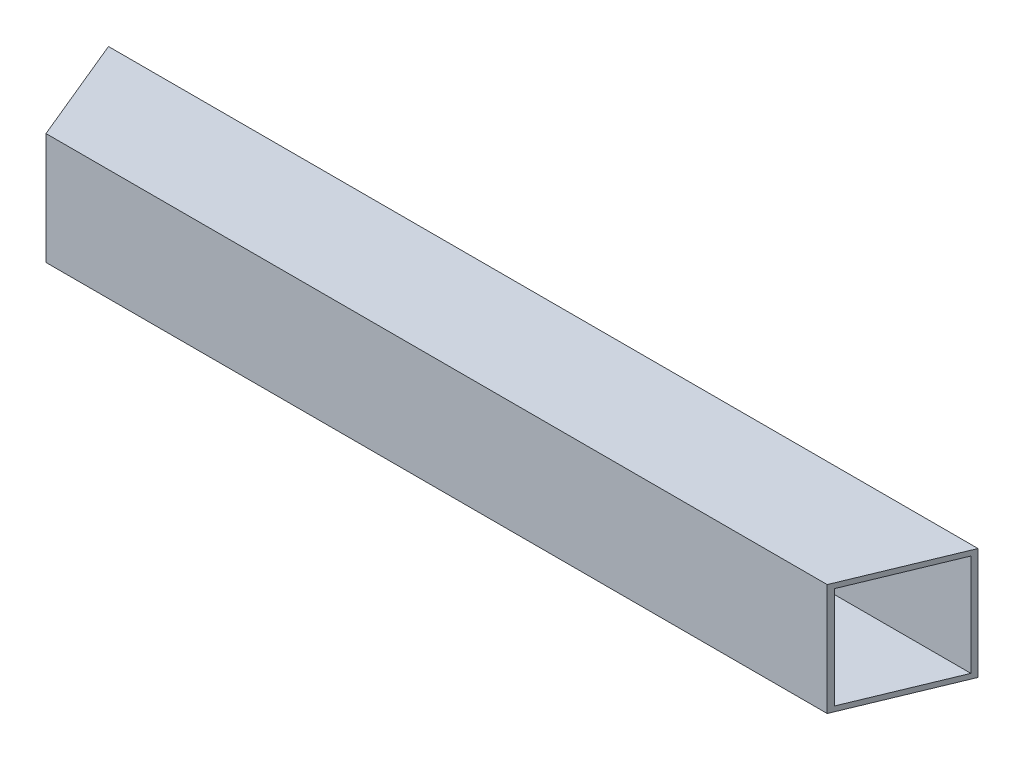
SolidWorks part; units mm, degrees
ref_plane "Front Plane" through (0, 0, 0) normal (0, 0, 1) x (1, 0, 0)
ref_plane "Top Plane" through (0, 0, 0) normal (0, 1, 0) x (1, 0, 0)
ref_plane "Right Plane" through (0, 0, 0) normal (1, 0, 0) x (0, 0, -1)
sketch "Sketch1" plane through (0, 0, 0) normal (0, 1, 0) x (1, 0, 0)
  line L0 (-103.5534, 250) -> (-93.0324, 224.6)
  line L1 (103.5534, 250) -> (-103.5534, 250) construction
  line L2 (-103.5534, 250) -> (-250, 103.5534) construction
  line L3 (-250, 103.5534) -> (-250, -103.5534) construction
  line L4 (-250, -103.5534) -> (-103.5534, -250) construction
  line L5 (-103.5534, -250) -> (103.5534, -250) construction
  line L6 (103.5534, -250) -> (250, -103.5534) construction
  line L7 (250, -103.5534) -> (250, 103.5534) construction
  line L8 (250, 103.5534) -> (103.5534, 250) construction
  line L9 (-93.0324, 224.6) -> (93.0324, 224.6)
  line L10 (93.0324, 224.6) -> (103.5534, 250)
  line L11 (-103.5534, 250) -> (103.5534, 250)
  circle A0 centre (0, 0) radius 250 construction
  dimension "D1" = 500
  dimension "D2" = 135
  dimension "D3" = 67.5
  dimension "D4" = 25.4
extrude "Boss-Extrude1" add sketch "Sketch1" along normal blind 1.2
sketch "Sketch2" plane through (0, 1.2, 0) normal (0, 1, 0) x (1, 0, 0)
  line L4 (93.0324, 224.6) -> (103.5534, 250)
  line L5 (103.5534, 250) -> (-103.5534, 250)
  line L6 (-103.5534, 250) -> (-93.0324, 224.6)
  line L7 (-93.0324, 224.6) -> (93.0324, 224.6)
  line L8 (93.0324, 224.6) -> (103.5534, 250)
  line L9 (103.5534, 250) -> (-103.5534, 250)
  line L10 (-103.5534, 250) -> (-93.0324, 224.6)
  line L11 (-93.0324, 224.6) -> (93.0324, 224.6)
  dimension "D1" = 0
extrude "Boss-Extrude2" add sketch "Sketch2" against normal blind 1.2 from offset 25.4 separate body
sketch "Sketch3" plane through (0, 1.2, 0) normal (0, 1, 0) x (1, 0, 0)
  line L0 (93.0324, 224.6) -> (103.5534, 250) construction
  line L1 (-103.5534, 250) -> (-93.0324, 224.6) construction
  line L2 (103.5534, 250) -> (-103.5534, 250) construction
  line L3 (-93.0324, 224.6) -> (93.0324, 224.6) construction
  line L4 (93.0324, 224.6) -> (93.5294, 225.8)
  line L5 (-103.5534, 250) -> (-103.0563, 248.8)
  line L6 (103.5534, 250) -> (-103.5534, 250)
  line L7 (-93.0324, 224.6) -> (93.0324, 224.6)
  line L8 (103.0563, 248.8) -> (-103.0563, 248.8)
  line L10 (-93.5294, 225.8) -> (93.5294, 225.8)
  line L12 (92.2306, 225.8) -> (101.7575, 248.8) construction
  line L13 (-101.7575, 248.8) -> (-92.2306, 225.8) construction
  line L14 (101.7575, 248.8) -> (-101.7575, 248.8) construction
  line L15 (-92.2306, 225.8) -> (92.2306, 225.8) construction
  line L16 (-93.5294, 225.8) -> (-93.0324, 224.6)
  line L17 (-103.5534, 250) -> (-93.0324, 224.6) construction
  line L18 (103.0563, 248.8) -> (103.5534, 250)
  line L19 (93.0324, 224.6) -> (103.5534, 250) construction
  point P8 (0, 0)
  dimension "D1" = 1.2
extrude "Boss-Extrude3" add sketch "Sketch3" along normal up to surface (24.2 mm away) up to face at (0, 25.4, -237.3)
equation "\"D3@Sketch1\"=\"D2@Sketch1\"/2"
